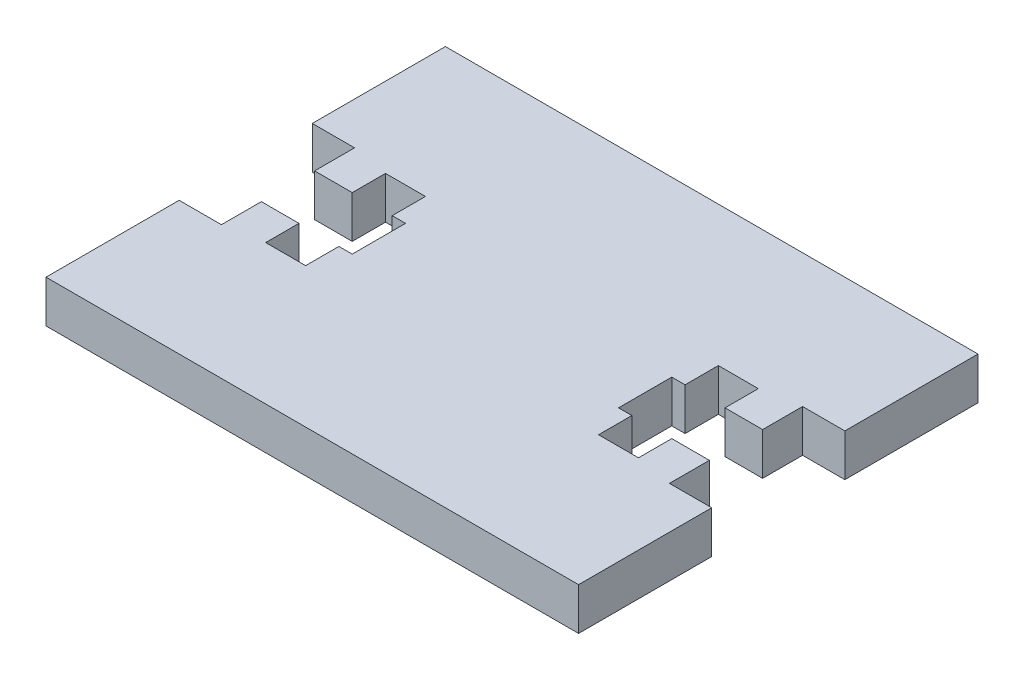
SolidWorks part; units mm, degrees
ref_plane "Front Plane" through (0, 0, 0) normal (0, 0, 1) x (1, 0, 0)
ref_plane "Top Plane" through (0, 0, 0) normal (0, 1, 0) x (1, 0, 0)
ref_plane "Right Plane" through (0, 0, 0) normal (1, 0, 0) x (0, 0, -1)
sketch "Sketch2" plane through (0, 0, 0) normal (0, 1, 0) x (1, 0, 0)
  line L0 (20, 20) -> (20, 30)
  line L1 (0, 0) -> (20, 0)
  line L2 (0, 0) -> (0, 30)
  line L3 (0, 30) -> (20, 30)
  line L4 (20, 0) -> (20, 10)
  line L6 (16.825, 13) -> (14, 13)
  line L8 (16.825, 17) -> (14, 17)
  line L9 (10, 13) -> (10, 17)
  line L10 (10, 13) -> (11, 13)
  line L11 (20, 10) -> (16.825, 10)
  line L13 (20, 20) -> (16.825, 20)
  line L14 (16.825, 10) -> (16.825, 13)
  line L15 (11, 17) -> (11, 19.5)
  line L16 (11, 10.5) -> (14, 10.5)
  line L17 (11, 10.5) -> (11, 13)
  line L18 (11, 19.5) -> (14, 19.5)
  line L19 (14, 10.5) -> (14, 13)
  line L20 (11, 17) -> (10, 17)
  line L22 (14, 17) -> (14, 19.5)
  line L23 (16.825, 17) -> (16.825, 20)
  dimension "D1" = 30
  dimension "D2" = 20
  dimension "D4" = 4
  dimension "D7" = 10
  dimension "D8" = 3.175
  dimension "D9" = 1
  dimension "D10" = 9
  dimension "D11" = 3
  dimension "D12" = 2.5
extrude "Boss-Extrude1" add sketch "Sketch2" along normal blind 3.175
mirror "Mirror1" about plane through (0, 3.175, 0) normal (1, 0, 0) of "Boss-Extrude1"
